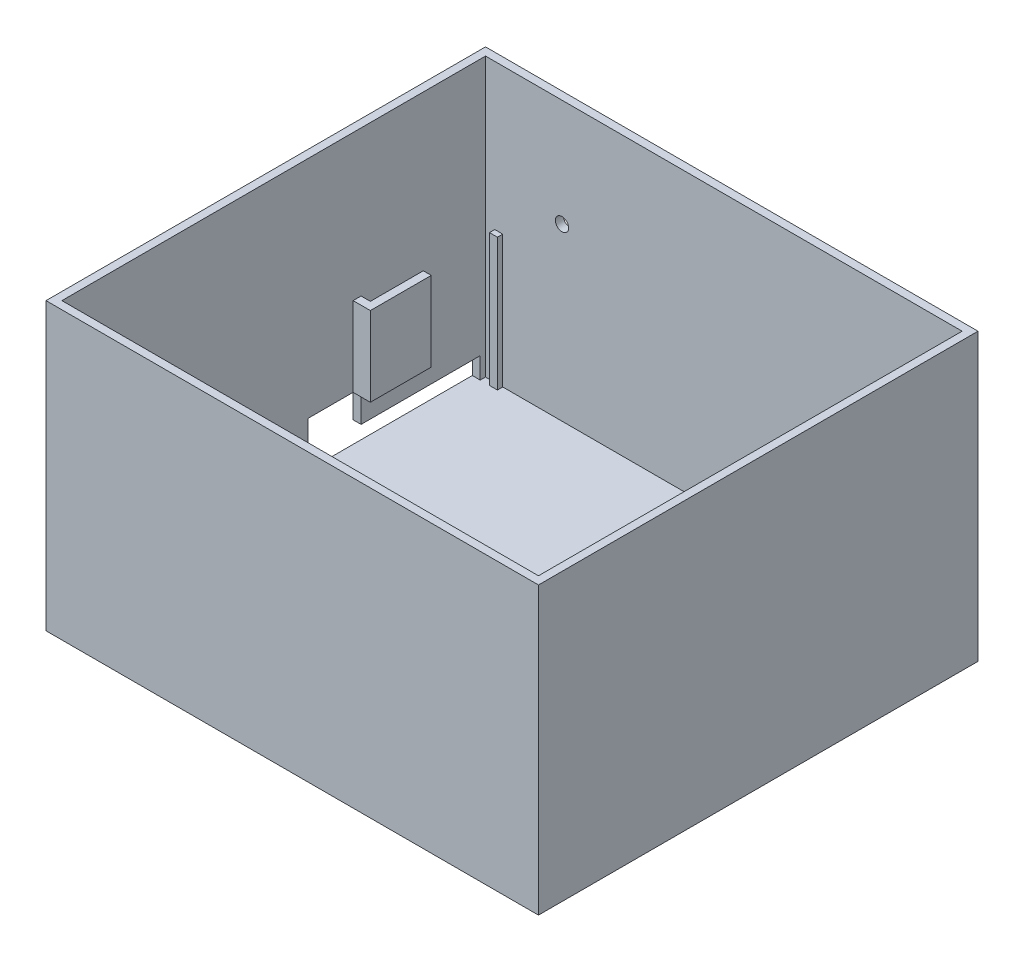
SolidWorks part; units mm, degrees
ref_plane "Front Plane" through (0, 0, 0) normal (0, 0, 1) x (1, 0, 0)
ref_plane "Top Plane" through (0, 0, 0) normal (0, 1, 0) x (1, 0, 0)
ref_plane "Right Plane" through (0, 0, 0) normal (1, 0, 0) x (0, 0, -1)
sketch "Sketch1" plane through (0, 0, 0) normal (0, 1, 0) x (1, 0, 0)
  line L1 (-89.25, 52.875) -> (96.75, 52.875)
  line L2 (-89.25, 52.875) -> (-89.25, -113.125)
  line L3 (-89.25, -113.125) -> (96.75, -113.125)
  line L4 (96.75, 52.875) -> (96.75, -113.125)
  dimension "D1" = 186
  dimension "D2" = 166
extrude "Boss-Extrude6" add sketch "Sketch1" along normal blind 3
sketch "Sketch7" plane through (0, 3, 0) normal (0, 1, 0) x (1, 0, 0)
  line L0 (96.75, -113.125) -> (96.75, 52.875) construction
  line L1 (-89.25, 52.875) -> (96.75, 52.875)
  line L2 (-89.25, 52.875) -> (-89.25, 49.875)
  line L3 (-89.25, 49.875) -> (96.75, 49.875)
  line L4 (96.75, 52.875) -> (96.75, 49.875)
  dimension "D1" = 3
sketch "Sketch8" plane through (0, 3, 0) normal (0, 1, 0) x (1, 0, 0)
  line L0 (-89.25, -113.125) -> (96.75, -113.125) construction
  line L1 (96.75, 49.875) -> (93.75, 49.875)
  line L2 (96.75, 49.875) -> (96.75, -113.125)
  line L3 (96.75, -113.125) -> (93.75, -113.125)
  line L4 (93.75, 49.875) -> (93.75, -113.125)
  dimension "D1" = 3
sketch "Sketch9" plane through (0, 3, 0) normal (0, 1, 0) x (1, 0, 0)
  line L0 (-89.25, 52.875) -> (-89.25, -113.125) construction
  line L1 (-89.25, -110.125) -> (93.75, -110.125)
  line L2 (-89.25, -110.125) -> (-89.25, -113.125)
  line L3 (-89.25, -113.125) -> (93.75, -113.125)
  line L4 (93.75, -110.125) -> (93.75, -113.125)
  dimension "D1" = 3
extrude "Boss-Extrude7" add sketch "Sketch9" along normal blind 105
extrude "Boss-Extrude8" add sketch "Sketch8" along normal blind 105
extrude "Boss-Extrude9" add sketch "Sketch7" along normal blind 105
sketch "Sketch11" plane through (0, 3, 0) normal (0, 1, 0) x (1, 0, 0)
  line L0 (93.75, -110.125) -> (-89.25, -110.125) construction
  line L1 (-89.25, 49.875) -> (-86.25, 49.875)
  line L2 (-89.25, 49.875) -> (-89.25, -110.125)
  line L3 (-89.25, -110.125) -> (-86.25, -110.125)
  line L4 (-86.25, 49.875) -> (-86.25, -110.125)
  dimension "D1" = 3
extrude "Boss-Extrude10" add sketch "Sketch11" along normal blind 105
sketch "Sketch12" plane through (0, 3, 0) normal (0, 1, 0) x (1, 0, 0)
  line L0 (-86.25, -110.125) -> (-86.25, 49.875) construction
  line L1 (-86.25, -51.125) -> (93.75, -51.125)
  line L2 (-86.25, -51.125) -> (-86.25, -54.125)
  line L3 (-86.25, -54.125) -> (93.75, -54.125)
  line L4 (93.75, -51.125) -> (93.75, -54.125)
  line L5 (93.75, 49.875) -> (93.75, -110.125) construction
  line L6 (-86.25, 49.875) -> (93.75, 49.875) construction
  dimension "D1" = 3
  dimension "D2" = 101
extrude "Boss-Extrude11" add sketch "Sketch12" along normal blind 20
sketch "Sketch13" plane through (-86.25, 0, 0) normal (1, 0, 0) x (0, 0, -1)
  line L0 (49.875, 108) -> (49.875, 3) construction
  line L1 (47.875, 3) -> (2.875, 3)
  line L2 (47.875, 3) -> (47.875, 11)
  line L3 (47.875, 11) -> (2.875, 11)
  line L4 (2.875, 3) -> (2.875, 11)
  line L5 (-51.125, 3) -> (49.875, 3) construction
  dimension "D1" = 8
  dimension "D2" = 45
  dimension "D3" = 2
  dimension "D4" = 0
extrude "Cut-Extrude5" cut sketch "Sketch13" against normal blind 3
sketch "Sketch18" plane through (-89.25, 0, 0) normal (-1, 0, 0) x (0, 0, 1)
  line L1 (-2.875, 3) -> (17.125, 3)
  line L2 (-2.875, 3) -> (-2.875, 23)
  line L3 (-2.875, 23) -> (17.125, 23)
  line L4 (17.125, 3) -> (17.125, 23)
  dimension "D1" = 20
  dimension "D2" = 20
sketch "Sketch20" plane through (0, 3, 0) normal (0, 1, 0) x (1, 0, 0)
  line L0 (-86.25, 49.875) -> (93.75, 49.875) construction
  line L1 (-82.75, 49.875) -> (-79.75, 49.875)
  line L2 (-82.75, 49.875) -> (-82.75, 47.875)
  line L3 (-82.75, 47.875) -> (-79.75, 47.875)
  line L4 (-79.75, 49.875) -> (-79.75, 47.875)
  line L5 (-86.25, 47.875) -> (-86.25, 49.875) construction
  dimension "D1" = 2
  dimension "D2" = 3
  dimension "D3" = 3.5
extrude "Boss-Extrude12" add sketch "Sketch20" along normal blind 50
extrude "Cut-Extrude6" cut sketch "Sketch18" against normal blind 3
sketch "Sketch22" plane through (-86.25, 0, 0) normal (1, 0, 0) x (0, 0, -1)
  line L1 (2.875, 23) -> (-0.125, 23)
  line L2 (2.875, 23) -> (2.875, 53)
  line L3 (2.875, 53) -> (-0.125, 53)
  line L4 (-0.125, 23) -> (-0.125, 53)
  dimension "D1" = 3
  dimension "D2" = 30
extrude "Boss-Extrude13" add sketch "Sketch22" along normal blind 6.5
sketch "Sketch23" plane through (0, 0, -2.875) normal (0, 0, -1) x (-1, 0, 0)
  line L0 (79.75, 23) -> (86.25, 23) construction
  line L1 (82.75, 23) -> (79.75, 23)
  line L2 (82.75, 23) -> (82.75, 53)
  line L3 (82.75, 53) -> (79.75, 53)
  line L4 (79.75, 23) -> (79.75, 53)
  dimension "D1" = 3
extrude "Boss-Extrude15" add sketch "Sketch23" along normal blind 20
sketch "Sketch24" plane through (0, 0, -49.875) normal (0, 0, 1) x (1, 0, 0)
  line L0 (-86.25, 108) -> (93.75, 108) construction
  circle A0 centre (-57.3659, 67.443) radius 2.5
  dimension "D1" = 5
  dimension "D2" = 40.557
extrude "Cut-Extrude8" cut sketch "Sketch24" against normal blind 10 contours A0
